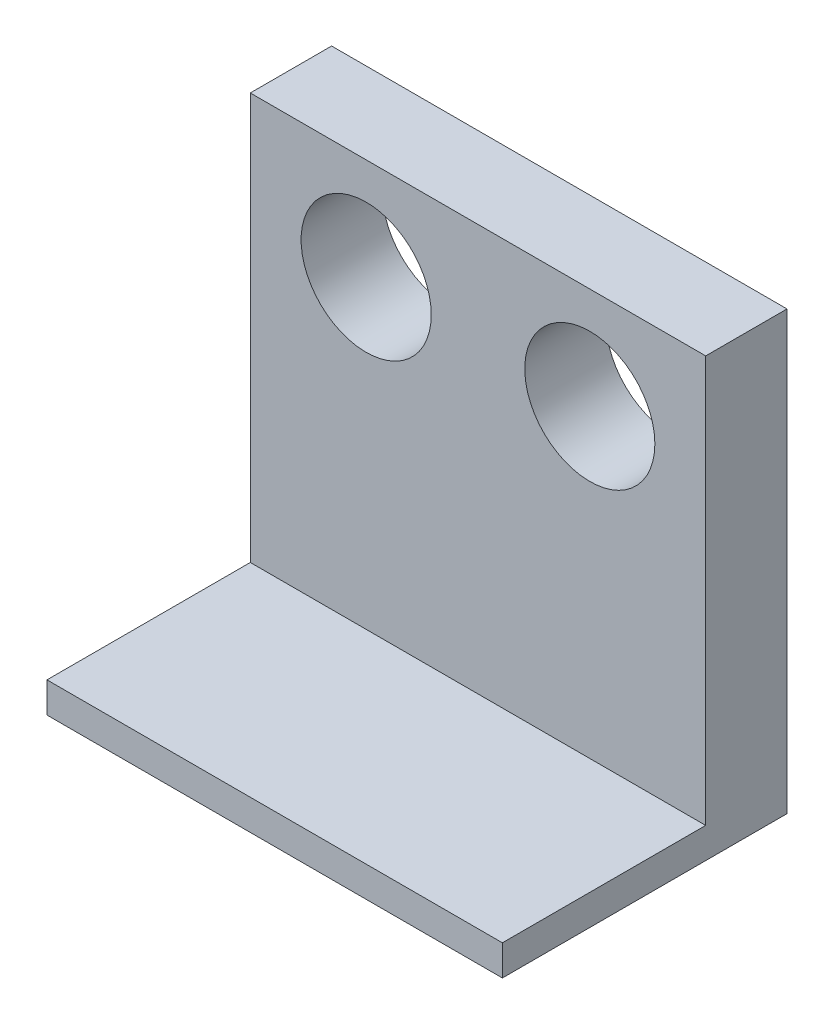
SolidWorks part; units mm, degrees
ref_plane "Alzado" through (0, 0, 0) normal (0, 0, 1) x (1, 0, 0)
ref_plane "Planta" through (0, 0, 0) normal (0, 1, 0) x (1, 0, 0)
ref_plane "Vista lateral" through (0, 0, 0) normal (1, 0, 0) x (0, 0, -1)
sketch "Croquis7" plane through (0, 0, 0) normal (0, 0, 1) x (1, 0, 0)
  line L0 (-22.4, 21.5) -> (-11, 21.5) construction
  line L1 (-22.4, -21.5) -> (22.4, -21.5)
  line L2 (-22.4, -21.5) -> (-22.4, 21.5)
  line L3 (-22.4, 21.5) -> (22.4, 21.5)
  line L4 (22.4, -21.5) -> (22.4, 21.5)
  line L5 (-22.4, -21.5) -> (22.4, 21.5) construction
  line L6 (-22.4, 21.5) -> (22.4, -21.5) construction
  line L7 (-11, 21.5) -> (-11, 11.5) construction
  line L8 (22.4, 21.5) -> (11, 21.5) construction
  line L9 (-11, 11.5) -> (11, 11.5) construction
  circle A0 centre (-11, 11.5) radius 6.4
  circle A1 centre (11, 11.5) radius 6.4
  circle A2 centre (11, 11.5) radius 10.875 construction
  circle A3 centre (-11, 11.5) radius 10.875 construction
  circle A4 centre (-11, 11.5) radius 7.9 construction
  point P0 (0, 0)
  dimension "D4" = 12.8
  dimension "D8" = 12.8
  dimension "D9" = 21.75
  dimension "D10" = 21.75
  dimension "D11" = 15.8
  dimension "D2" = 43
  dimension "D3" = 11.4
  dimension "D5" = 10
  dimension "D6" = 22
  dimension "D7" = 10
  dimension "D12" = 11.4
extrude "Saliente-Extruir4" add sketch "Croquis7" along normal blind 8
sketch "Croquis8" plane through (0, 0, 8) normal (0, 0, 1) x (1, 0, 0)
  line L0 (22.4, -21.5) -> (22.4, 21.5) construction
  line L1 (-22.4, -21.5) -> (22.4, -21.5)
  line L2 (-22.4, -21.5) -> (-22.4, -18.5)
  line L3 (-22.4, -18.5) -> (22.4, -18.5)
  line L4 (22.4, -21.5) -> (22.4, -18.5)
  dimension "D1" = 3
extrude "Saliente-Extruir5" add sketch "Croquis8" along normal blind 20
sketch "Sketch1" plane through (0, 0, 8) normal (0, 0, 1) x (1, 0, 0)
